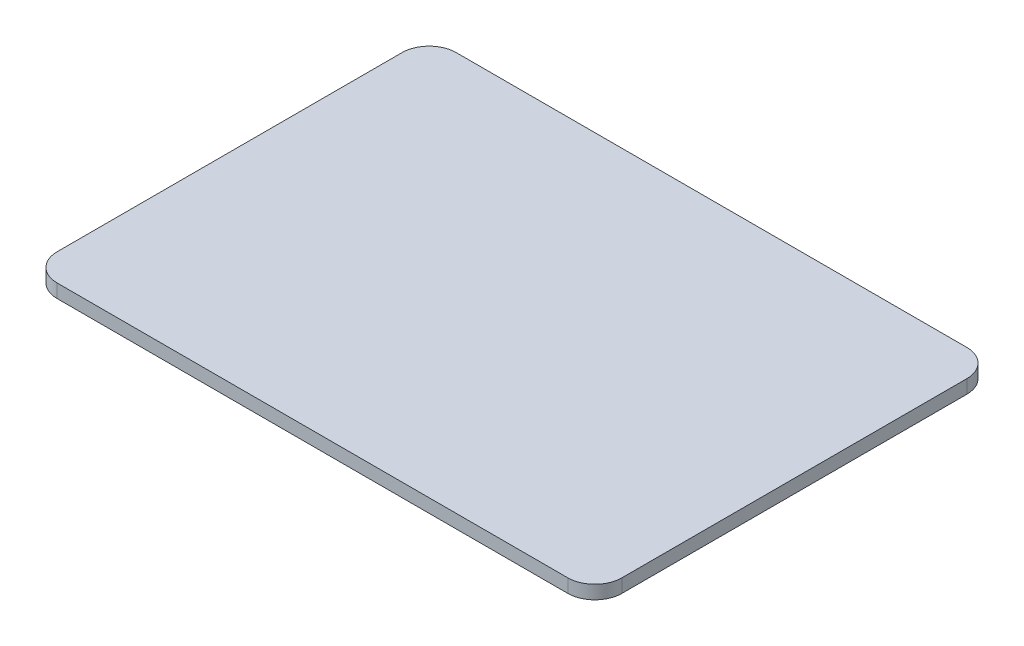
SolidWorks part; units mm, degrees
material "ABS"
ref_plane "Front Plane" through (0, 0, 0) normal (0, 0, 1) x (1, 0, 0)
ref_plane "Top Plane" through (0, 0, 0) normal (0, 1, 0) x (1, 0, 0)
ref_plane "Right Plane" through (0, 0, 0) normal (1, 0, 0) x (0, 0, -1)
sketch "Sketch1" plane through (0, 0, 0) normal (0, 1, 0) x (1, 0, 0)
  line L1 (-132.5562, -93.6625) -> (132.5563, -93.6625)
  line L2 (-132.5562, -93.6625) -> (-132.5562, 93.6625)
  line L3 (-132.5562, 93.6625) -> (132.5563, 93.6625)
  line L4 (132.5563, -93.6625) -> (132.5563, 93.6625)
  line L5 (-132.5562, -93.6625) -> (132.5563, 93.6625) construction
  line L6 (-132.5562, 93.6625) -> (132.5563, -93.6625) construction
  point P0 (0, 0)
  dimension "D1" = 265.1125
  dimension "D2" = 187.325
extrude "Boss-Extrude1" add sketch "Sketch1" along normal blind 6.35
fillet "Fillet1" radius 12.7 4 edges at (-132.5562, 3.175, -93.6625) (132.5563, 3.175, -93.6625) (132.5563, 3.175, 93.6625) (-132.5562, 3.175, 93.6625)
